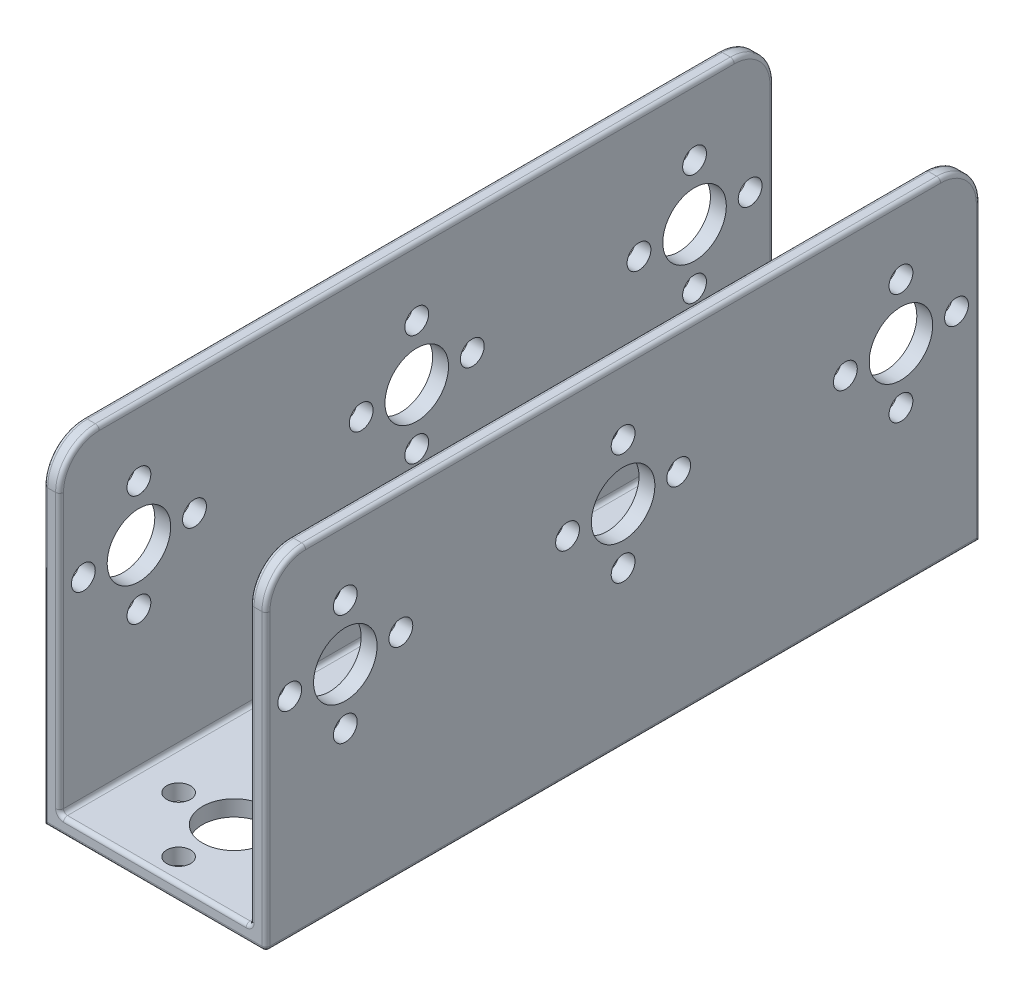
SolidWorks part; units mm, degrees
ref_plane "Front Plane" through (0, 0, 0) normal (0, 0, 1) x (1, 0, 0)
ref_plane "Top Plane" through (0, 0, 0) normal (0, 1, 0) x (1, 0, 0)
ref_plane "Right Plane" through (0, 0, 0) normal (1, 0, 0) x (0, 0, -1)
sketch "Sketch1" plane through (0, 0, 0) normal (0, 1, 0) x (1, 0, 0)
  line L1 (-14, 45) -> (14, 45)
  line L2 (-14, 45) -> (-14, -45)
  line L3 (-14, -45) -> (14, -45)
  line L4 (14, 45) -> (14, -45)
  line L5 (-14, 45) -> (14, -45) construction
  line L6 (-14, -45) -> (14, 45) construction
  point P0 (0, 0)
  dimension "D1" = 28
  dimension "D2" = 90
extrude "Boss-Extrude1" add sketch "Sketch1" along normal blind 2
sketch "Sketch2" plane through (0, 2, 0) normal (0, 1, 0) x (1, 0, 0)
  line L0 (-14, -45) -> (14, -45) construction
  line L1 (14, 45) -> (12, 45)
  line L2 (14, 45) -> (14, -45)
  line L3 (14, -45) -> (12, -45)
  line L4 (12, 45) -> (12, -45)
  line L5 (14, 45) -> (-14, 45) construction
  line L10 (-14, -45) -> (-12, -45)
  line L11 (-14, -45) -> (-14, 45)
  line L12 (-14, 45) -> (-12, 45)
  line L13 (-12, -45) -> (-12, 45)
  dimension "D1" = 2
  dimension "D2" = 2
extrude "Boss-Extrude2" add sketch "Sketch2" along normal blind 40
fillet "Fillet2" radius 5 4 edges at (13, 42, -45) (-13, 42, -45) (-13, 42, 45) (13, 42, 45)
fillet "Fillet3" radius 0.5 26 edges at (12, 19.5, -45) (-14, 18.5, -45) (-12, 2, 0) (-14, 42, 0) (-12, 42, 0) (-12, 19.5, -45) (-12, 19.5, 45) (12, 2, 0) (14, 42, 0) (12, 42, 0) (12, 19.5, 45) (14, 0, 0) (0, 0, 45) (0, 2, -45) (0, 2, 45) (14, 18.5, 45) (-14, 18.5, 45) (14, 18.5, -45) (12, 40.5355, 43.5355) (12, 40.5355, -43.5355) (14, 40.5355, 43.5355) (14, 40.5355, -43.5355) (-14, 40.5355, 43.5355) (-14, 40.5355, -43.5355) (-12, 40.5355, 43.5355) (-12, 40.5355, -43.5355)
hole_wizard "Ø8.0mm Dowel Hole1" positions "Sketch8" profile "Sketch9" hole size "Ø8.0" standard "ISO" end condition through all
sketch "Sketch8" plane through (14, 0, 0) normal (1, 0, 0) x (0, 0, -1)
  line L0 (40, 41.5) -> (-40, 41.5) construction
  point P8 (0, 26.5)
  point P10 (-35, 26.5)
  point P14 (35, 26.5)
  dimension "D1" = 15
  dimension "D2" = 35
  dimension "D3" = 35
sketch "Sketch9" plane through (14, 26.5, 0) normal (0, 1, 0) x (0, 0, -1)
  line L0 (0, 0) -> (0, 28)
  line L1 (0, 28) -> (4, 28)
  line L2 (4, 28) -> (4, 0)
  line L5 (4, 0) -> (0, 0)
  line L11 (0, -6.35) -> (0, 107.95) construction
  dimension "Thru Hole Dia." = 8
  dimension "Thru Hole Depth" = 28
hole_wizard "Ø3.0mm Dowel Hole2" positions "Sketch14" profile "Sketch15" hole size "Ø3.0" standard "ISO" end condition through all
sketch "Sketch14" plane through (14, 0, 0) normal (1, 0, 0) x (0, 0, -1)
  line L0 (-44.5, 37) -> (-44.5, 0.5) construction
  circle A0 centre (-35, 26.5) radius 4 construction
  point P0 (-35, 33.5)
  point P10 (-28, 26.5)
  point P11 (-35, 19.5)
  point P12 (-42, 26.5)
  point P13 (-35, 26.5)
  point P20 (0, 33.5)
  point P21 (7, 26.5)
  point P22 (0, 19.5)
  point P23 (-7, 26.5)
  point P24 (35, 33.5)
  point P25 (42, 26.5)
  point P26 (35, 19.5)
  point P27 (28, 26.5)
  point P30 (0, 26.5)
  point P33 (35, 26.5)
  point P36 (0, 0)
  point P39 (0, 0)
  point P40 (0, 0)
  point P41 (0, 0)
  point P42 (0, 0)
  dimension "D1" = 7
  dimension "D4" = 9.5
  dimension "D3" = 3
  dimension "D2" = 4
sketch "Sketch15" plane through (14, 33.5, 35) normal (0, 1, 0) x (0, 0, -1)
  line L0 (0, 0) -> (0, 28)
  line L1 (0, 28) -> (1.5, 28)
  line L2 (1.5, 28) -> (1.5, 0)
  line L5 (1.5, 0) -> (0, 0)
  line L11 (0, -6.35) -> (0, 107.95) construction
  dimension "Thru Hole Dia." = 3
  dimension "Thru Hole Depth" = 28
hole_wizard "Ø8.0mm Dowel Hole2" positions "Sketch17" profile "Sketch19" hole size "Ø8.0" standard "ISO"
sketch "Sketch17" plane through (0, 0, 0) normal (0, -1, 0) x (-1, 0, 0)
  point P0 (0, 0)
  point P3 (0, 35)
  point P5 (0, -35)
  dimension "D1" = 35
  dimension "D2" = 35
sketch "Sketch19" plane through (0, 0, 0) normal (1, 0, 0) x (0, 0, -1)
  line L0 (0, 0) -> (0, 5.4034)
  line L1 (0, 5.4034) -> (4, 3)
  line L2 (4, 3) -> (4, 0)
  line L5 (4, 0) -> (0, 0)
  line L10 (0, 5.4034) -> (-4, 3) construction
  line L11 (0, -6.35) -> (0, 107.95) construction
  dimension "Hole Dia." = 8
  dimension "Hole Depth" = 3
  dimension "Drill Angle" = 118
hole_wizard "Ø3.0mm Dowel Hole3" positions "Sketch22" profile "Sketch23" hole size "Ø3.0" standard "ISO" end condition through all
sketch "Sketch22" plane through (0, 0, 0) normal (0, -1, 0) x (-1, 0, 0)
  point P0 (0, -7)
  point P2 (0, -35)
  point P5 (0, -28)
  point P7 (0, 35)
  point P10 (0, 28)
  point P19 (7, 0)
  point P20 (0, 7)
  point P21 (-7, 0)
  point P22 (0, 0)
  point P30 (7, -35)
  point P31 (0, -42)
  point P32 (-7, -35)
  point P33 (0, -35)
  point P40 (-7, 35)
  point P41 (0, 42)
  point P42 (7, 35)
  point P43 (0, 35)
  dimension "D1" = 7
  dimension "D2" = 7
  dimension "D3" = 7
  dimension "D4" = 4
sketch "Sketch23" plane through (0, 0, 7) normal (1, 0, 0) x (0, 0, -1)
  line L0 (0, 0) -> (0, 42)
  line L1 (0, 42) -> (1.5, 42)
  line L2 (1.5, 42) -> (1.5, 0)
  line L5 (1.5, 0) -> (0, 0)
  line L11 (0, -6.35) -> (0, 107.95) construction
  dimension "Thru Hole Dia." = 3
  dimension "Thru Hole Depth" = 42
